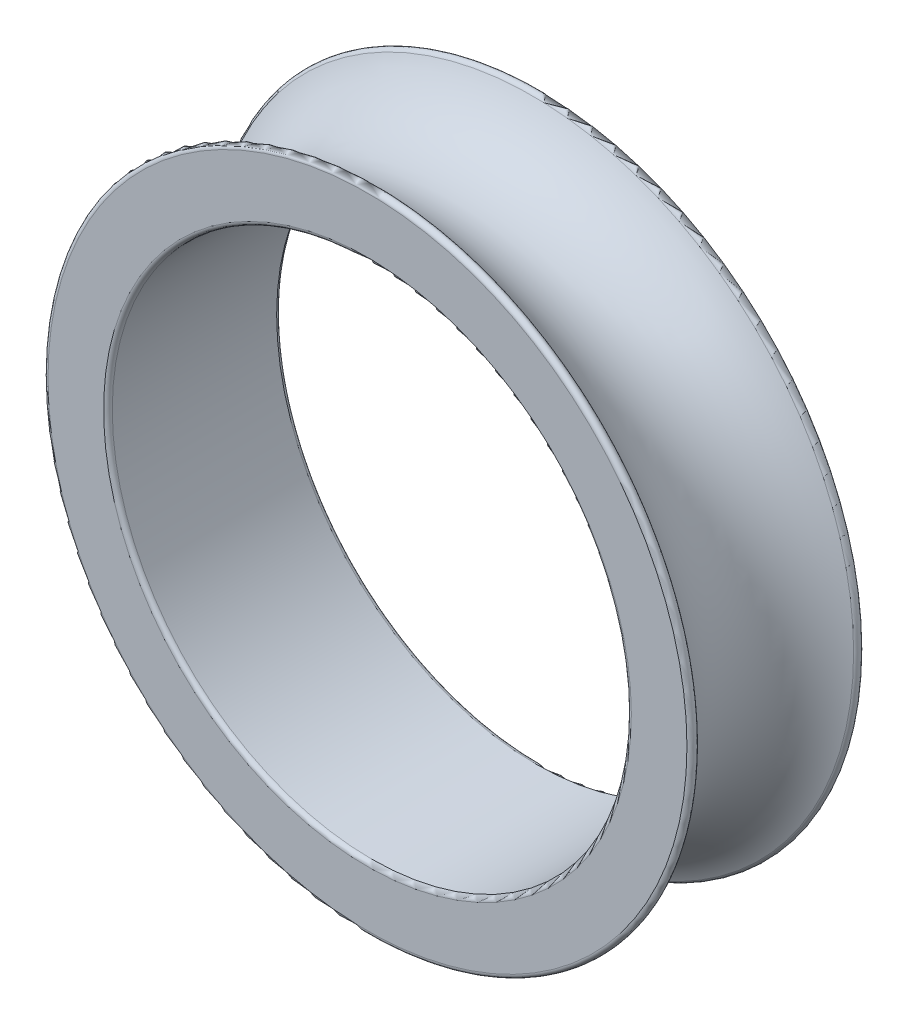
SolidWorks part; units mm, degrees
ref_plane "Front Plane" through (0, 0, 0) normal (0, 0, 1) x (1, 0, 0)
ref_plane "Top Plane" through (0, 0, 0) normal (0, 1, 0) x (1, 0, 0)
ref_plane "Right Plane" through (0, 0, 0) normal (1, 0, 0) x (0, 0, -1)
sketch "Sketch1" plane through (0, 0, 0) normal (0, 0, 1) x (1, 0, 0)
  circle A0 centre (0, 0) radius 21
  dimension "D1" = 42
extrude "Boss-Extrude1" add sketch "Sketch1" along normal blind 10
sketch "Sketch2" plane through (0, 0, 10) normal (0, 0, 1) x (1, 0, 0)
  circle A0 centre (0, 0) radius 15
  dimension "D1" = 30
extrude "Cut-Extrude1" cut sketch "Sketch2" against normal through all both and the other way through all
sketch "Sketch3" plane through (0, 0, 0) normal (0, 1, 0) x (1, 0, 0)
  line L0 (0, 0) -> (0, -10) construction
  line L1 (-15, -10) -> (15, -10) construction
  line L2 (-21, 0) -> (-21, -10)
  arc A0 (-21, 0) -> (-21, -10) centre (-20.7179, -5) cw
  point P10 (-15.71, -5)
  dimension "D1" = 15.71
revolve "Cut-Revolve1" cut sketch "Sketch3" angle 360 about L0
fillet "Fillet1" radius 0.25 4 edges at (15, 0, 10) (-20.4359, 0, 10) (15, 0, 0) (-20.4359, 0, 0)
equation "\"D1@Sketch3\"=31.42/2"
